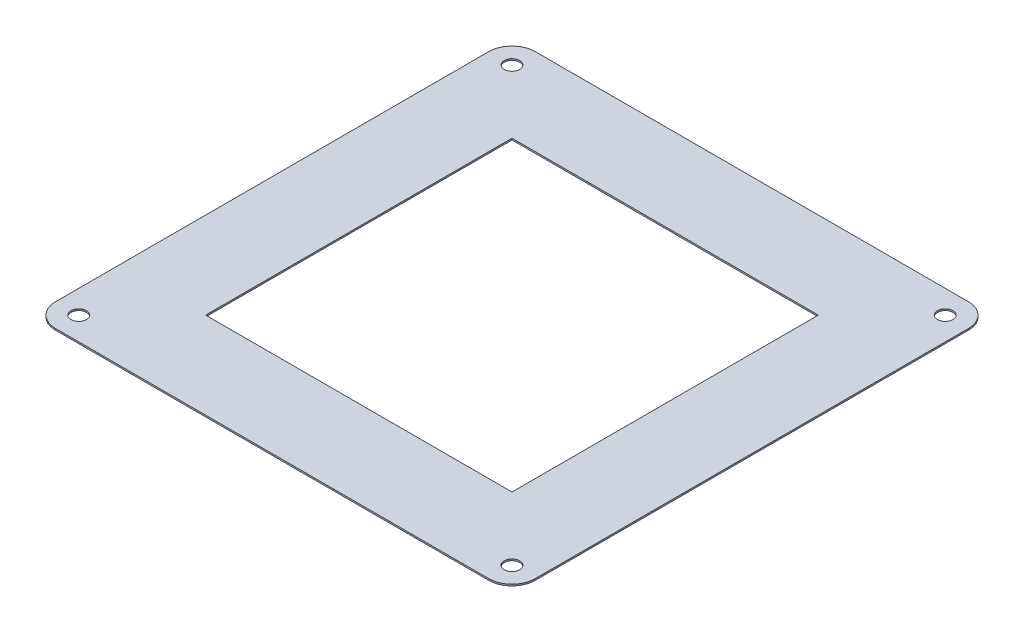
SolidWorks part; units mm, degrees
ref_plane "Alzado" through (0, 0, 0) normal (0, 0, 1) x (1, 0, 0)
ref_plane "Planta" through (0, 0, 0) normal (0, 1, 0) x (1, 0, 0)
ref_plane "Vista lateral" through (0, 0, 0) normal (1, 0, 0) x (0, 0, -1)
sketch "Croquis1" plane through (0, 0, 0) normal (0, 1, 0) x (1, 0, 0)
  line L0 (87.5, 17.5) -> (87.5, 10) construction
  line L1 (17.5, 10) -> (157.5, 10)
  line L2 (10, 17.5) -> (10, 157.5)
  line L3 (17.5, 165) -> (157.5, 165)
  line L4 (165, 17.5) -> (165, 157.5)
  line L5 (17.5, 17.5) -> (157.5, 17.5) construction
  line L6 (17.5, 17.5) -> (17.5, 157.5) construction
  line L7 (17.5, 157.5) -> (157.5, 157.5) construction
  line L8 (157.5, 17.5) -> (157.5, 157.5) construction
  line L9 (157.5, 87.5) -> (165, 87.5) construction
  line L10 (17.5, 157.5) -> (157.5, 17.5) construction
  line L12 (87.5, 87.5) -> (157.5, 157.5) construction
  circle A0 centre (17.5, 157.5) radius 2.5
  circle A1 centre (157.5, 157.5) radius 2.5
  circle A2 centre (157.5, 17.5) radius 2.5
  circle A3 centre (17.5, 17.5) radius 2.5
  arc A4 (17.5, 165) -> (10, 157.5) centre (17.5, 157.5) ccw
  arc A5 (165, 157.5) -> (157.5, 165) centre (157.5, 157.5) ccw
  arc A6 (157.5, 10) -> (165, 17.5) centre (157.5, 17.5) ccw
  arc A7 (10, 17.5) -> (17.5, 10) centre (17.5, 17.5) ccw
  dimension "D3" = 5
  dimension "D1" = 15
  dimension "D2" = 140
  dimension "D4" = 4
extrude "Saliente-Extruir1" add sketch "Croquis1" along normal blind 0.5
sketch "Croquis2" plane through (0, 0.5, 0) normal (0, 1, 0) x (1, 0, 0)
  line L0 (10, 87.5) -> (165, 87.5) construction
  line L1 (10, 157.5) -> (10, 17.5) construction
  line L2 (165, 17.5) -> (165, 157.5) construction
  line L3 (87.5, 10) -> (87.5, 165) construction
  line L4 (17.5, 10) -> (157.5, 10) construction
  line L5 (157.5, 165) -> (17.5, 165) construction
  line L7 (38, 38) -> (137, 38)
  line L8 (38, 38) -> (38, 137)
  line L9 (38, 137) -> (137, 137)
  line L10 (137, 38) -> (137, 137)
  line L11 (38, 38) -> (137, 137) construction
  line L12 (38, 137) -> (137, 38) construction
  point P12 (87.5, 87.5)
  dimension "D1" = 99
extrude "Cortar-Extruir1" cut sketch "Croquis2" against normal blind 10
